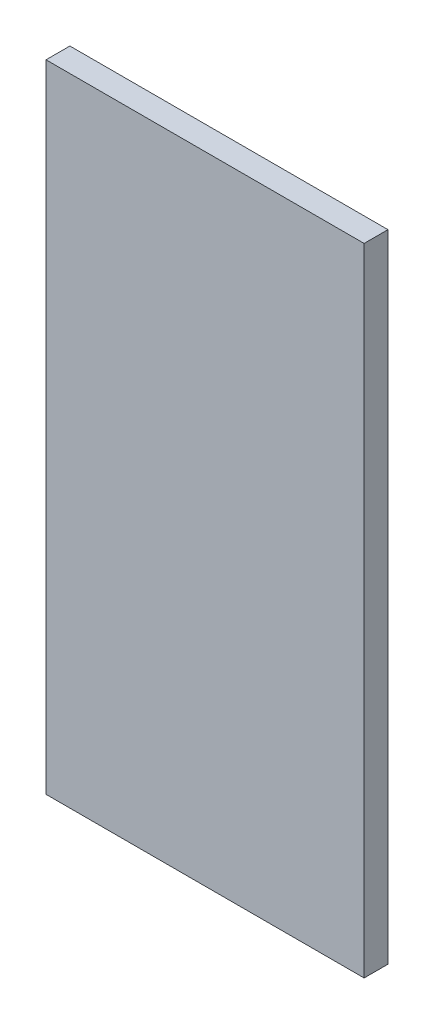
SolidWorks part; units mm, degrees
ref_plane "前视基准面" through (0, 0, 0) normal (0, 0, 1) x (1, 0, 0)
ref_plane "上视基准面" through (0, 0, 0) normal (0, 1, 0) x (1, 0, 0)
ref_plane "右视基准面" through (0, 0, 0) normal (1, 0, 0) x (0, 0, -1)
sketch "草图1" plane through (0, 0, 0) normal (0, 0, 1) x (1, 0, 0)
  line L1 (-10, -20) -> (10, -20)
  line L2 (-10, -20) -> (-10, 20)
  line L3 (-10, 20) -> (10, 20)
  line L4 (10, -20) -> (10, 20)
  line L5 (-10, -20) -> (10, 20) construction
  line L6 (-10, 20) -> (10, -20) construction
  point P0 (0, 0)
  dimension "D1" = 40
  dimension "D2" = 20
extrude "凸台-拉伸1" add sketch "草图1" along normal blind 1.5
